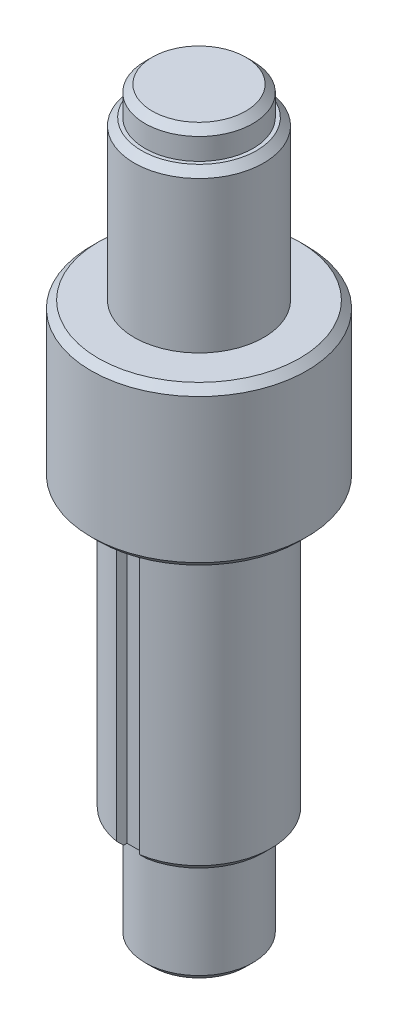
SolidWorks part; units mm, degrees
ref_plane "Front Plane" through (0, 0, 0) normal (0, 0, 1) x (1, 0, 0)
ref_plane "Top Plane" through (0, 0, 0) normal (0, 1, 0) x (1, 0, 0)
ref_plane "Right Plane" through (0, 0, 0) normal (1, 0, 0) x (0, 0, -1)
sketch "Sketch1" plane through (0, 0, 0) normal (0, 0, 1) x (1, 0, 0)
  line L0 (0, 0) -> (7.5, 0)
  line L1 (7.5, 0) -> (7.5, 15)
  line L2 (7.5, 15) -> (10, 15)
  line L3 (10, 15) -> (10, 55)
  line L4 (10, 55) -> (15, 55)
  line L5 (15, 55) -> (15, 77)
  line L6 (15, 77) -> (9, 77)
  line L7 (9, 77) -> (9, 99)
  line L8 (9, 99) -> (7.5, 99)
  line L9 (7.5, 99) -> (7.5, 103)
  line L10 (7.5, 103) -> (0, 103)
  line L11 (0, 103) -> (0, 0)
  line L12 (10, 35) -> (54.7446, 35) construction
  dimension "D1" = 7.5
  dimension "D2" = 10
  dimension "D3" = 15
  dimension "D4" = 40
  dimension "D5" = 15
  dimension "D6" = 22
  dimension "D7" = 22
  dimension "D8" = 68
  dimension "D9" = 9
revolve "Revolve1" add sketch "Sketch1" angle 360 about L11
sketch "Sketch2" plane through (0, 15, 0) normal (0, -1, 0) x (1, 0, 0)
  line L1 (-1.625, 11.625) -> (1.625, 11.625)
  line L2 (-1.625, 11.625) -> (-1.625, 8.375)
  line L3 (-1.625, 8.375) -> (1.625, 8.375)
  line L4 (1.625, 11.625) -> (1.625, 8.375)
  line L5 (-1.625, 11.625) -> (1.625, 8.375) construction
  line L6 (-1.625, 8.375) -> (1.625, 11.625) construction
  circle A0 centre (0, 0) radius 10 construction
  point P0 (0, 10)
  dimension "D1" = 3.25
extrude "Cut-Extrude1" cut sketch "Sketch2" against normal up to surface (40 mm away) up to face at (0, 55, 15)
chamfer "Chamfer1" distance 1 angle 45 6 edges at (0, 103, 7.5) (0, 0, 7.5) (0, 77, 15) (0, 55, 15) (0, 99, 9) (0, 15, -10)
sketch "Sketch3" plane through (0, 99, 0) normal (0, 1, 0) x (1, 0, 0)
  line L5 (-1.625, 10.625) -> (1.625, 10.625)
  line L6 (-1.625, 10.625) -> (-1.625, 7.375)
  line L7 (-1.625, 7.375) -> (1.625, 7.375)
  line L8 (1.625, 10.625) -> (1.625, 7.375)
  line L9 (-1.625, 10.625) -> (1.625, 7.375) construction
  line L10 (-1.625, 7.375) -> (1.625, 10.625) construction
  circle A1 centre (0, 0) radius 9 construction
  circle A2 centre (0, 0) radius 9 construction
  point P0 (0, 9)
  dimension "D1" = 3.25
extrude "Cut-Extrude2" cut sketch "Sketch3" against normal up to surface (22 mm away) up to face at (0, 77, -14)
